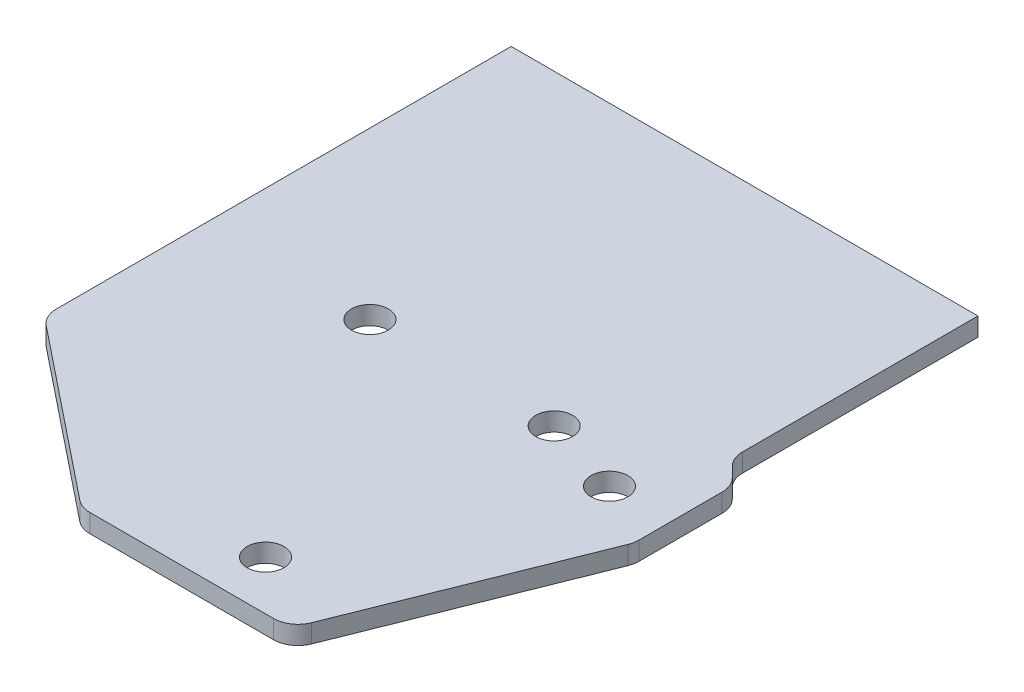
SolidWorks part; units mm, degrees
ref_plane "Plano frontal" through (0, 0, 0) normal (0, 0, 1) x (1, 0, 0)
ref_plane "Plano superior" through (0, 0, 0) normal (0, 1, 0) x (1, 0, 0)
ref_plane "Plano direito" through (0, 0, 0) normal (1, 0, 0) x (0, 0, -1)
sketch "Esboço1" plane through (0, 0, 0) normal (0, 1, 0) x (1, 0, 0)
  line L0 (-19, -12.0388) -> (-19, 25)
  line L1 (-3.2984, -25) -> (13, -25)
  line L2 (-19, 25) -> (19, 25)
  line L3 (19, 5.8284) -> (19, 25)
  line L6 (-1.9655, 25) -> (-1.9655, 44.9942) construction
  line L8 (20.4142, 3.5858) -> (19.5858, 4.4142)
  line L14 (21, 2.1716) -> (21, -4.6148)
  line L19 (-18.2494, -13.6005) -> (-4.5478, -24.5617)
  line L24 (13.5029, -23.7428) -> (20.857, -5.3576)
  line L25 (11.6459, -25) -> (4.712, -25)
  circle A0 centre (16, -2) radius 1.5
  circle A1 centre (9.5, 0) radius 1.5
  circle A2 centre (-5.5, 0) radius 1.5
  circle A3 centre (7, -21) radius 1.5
  arc A4 (-19, -12.0388) -> (-18.2494, -13.6005) centre (-17, -12.0388) ccw
  arc A5 (-4.5478, -24.5617) -> (-3.2984, -25) centre (-3.2984, -23) ccw
  arc A6 (13.5029, -23.7428) -> (11.6459, -25) centre (11.6459, -23) cw
  arc A7 (20.857, -5.3576) -> (21, -4.6148) centre (19, -4.6148) ccw
  arc A8 (19, 5.8284) -> (19.5858, 4.4142) centre (21, 5.8284) ccw
  arc A9 (20.4142, 3.5858) -> (21, 2.1716) centre (19, 2.1716) cw
  point P1 (0, 0)
  point P27 (-19, -13)
  point P30 (-4, -25)
  point P36 (21, -5)
  point P39 (19, 5)
  point P42 (21, 3)
  dimension "D9" = 3
  dimension "D18" = 2
  dimension "D1" = 38
  dimension "D2" = 17
  dimension "D3" = 38
  dimension "D4" = 21.5407
  dimension "D5" = 2
  dimension "D6" = 8
  dimension "D7" = 20
  dimension "D8" = 19.2094
  dimension "D10" = 5
  dimension "D11" = 5
  dimension "D12" = 25
  dimension "D13" = 11.5
  dimension "D14" = 25
  dimension "D15" = 15
  dimension "D16" = 6
  dimension "D17" = 4
extrude "Ressalto-extrusão1" add sketch "Esboço1" along normal blind 1.5 contours L1 L24 L14 L8 L3 L2 L0 L19 A3 A2 A1 A0
